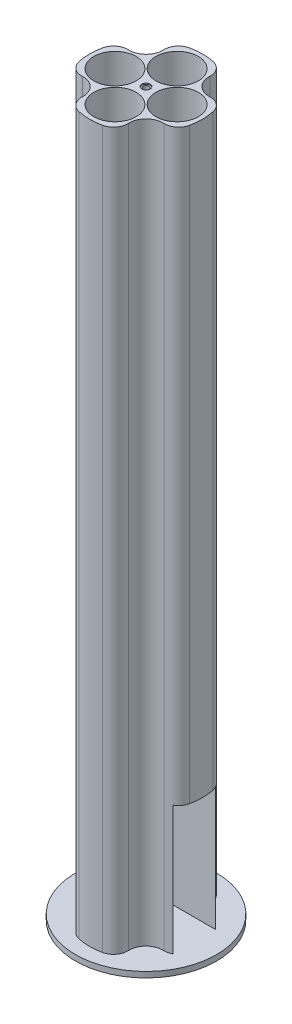
SolidWorks part; units mm, degrees
material "Acrylic (Medium-high impact)"
ref_plane "Front Plane" through (0, 0, 0) normal (0, 0, 1) x (1, 0, 0)
ref_plane "Top Plane" through (0, 0, 0) normal (0, 1, 0) x (1, 0, 0)
ref_plane "Right Plane" through (0, 0, 0) normal (1, 0, 0) x (0, 0, -1)
sketch "Sketch1" plane through (0, 0, 0) normal (0, 1, 0) x (1, 0, 0)
  circle A0 centre (0, 0) radius 100
  dimension "D1" = 200
extrude "Boss-Extrude2" add sketch "Sketch1" along normal blind 1120 contours A0
sketch "Sketch4" plane through (0, 1120, 0) normal (0, 1, 0) x (1, 0, 0)
  line L0 (0, 0) -> (0, -55) construction
  line L1 (0, 0) -> (55, 0) construction
  line L2 (0, 0) -> (0, 55) construction
  line L3 (0, 0) -> (-55, 0) construction
  circle A0 centre (55, 0) radius 37.5
  circle A1 centre (0, 55) radius 37.5
  circle A2 centre (-55, 0) radius 37.5
  circle A3 centre (0, -55) radius 37.5
  dimension "D2" = 75
  dimension "D1" = 55
extrude "Cut-Extrude1" cut sketch "Sketch4" against normal blind 1100 contours A1 | A2 | A0 | A3
sketch "Sketch6" plane through (0, 1120, 0) normal (0, 1, 0) x (1, 0, 0)
  line L0 (0, 0) -> (-70.7107, 70.7107) construction
  circle A0 centre (0, 0) radius 15
  circle A1 centre (-70.7107, 70.7107) radius 30.03
  circle A2 centre (0, 0) radius 100
  circle A3 centre (0, 0) radius 100
  circle A4 centre (0, 0) radius 15
  circle A5 centre (70.7107, 70.7107) radius 30.03
  circle A6 centre (0, 0) radius 15
  circle A7 centre (70.7107, -70.7107) radius 30.03
  circle A8 centre (0, 0) radius 15
  circle A9 centre (-70.7107, -70.7107) radius 30.03
  point P20 (0, 0)
  circle M8 centre (0, 0) radius 100
  dimension "D1" = 30
  dimension "D2" = 0
  dimension "D3" = 4
extrude "Cut-Extrude2" cut sketch "Sketch6" against normal through all contours L0 A1 M8 | A1 L0 A3 | A3 A5 | A3 A7 | A3 A9
sketch "Sketch7" plane through (0, 1120, 0) normal (0, 1, 0) x (1, 0, 0)
  circle A0 centre (0, 0) radius 5
  dimension "D1" = 10
extrude "Cut-Extrude3" cut sketch "Sketch7" against normal blind 1200
fillet "Fillet1" radius 25 8 edges at (-88.516, 560, 46.5286) (-46.5286, 560, 88.516) (-46.5286, 560, -88.516) (-88.516, 560, -46.5286) (88.516, 560, -46.5286) (46.5286, 560, -88.516) (46.5286, 560, 88.516) (88.516, 560, 46.5286)
sketch "Sketch8" plane through (0, 1120, 0) normal (0, 1, 0) x (1, 0, 0)
  line L1 (147.8756, 155.206) -> (-128.3047, 155.206)
  line L2 (147.8756, 155.206) -> (147.8756, -161.0426)
  line L3 (147.8756, -161.0426) -> (-128.3047, -161.0426)
  line L4 (-128.3047, 155.206) -> (-128.3047, -161.0426)
extrude "Cut-Extrude4" cut sketch "Sketch8" against normal blind 65
sketch "Sketch9" plane through (0, 1055, 0) normal (0, 1, 0) x (1, 0, 0)
  circle A0 centre (0, 0) radius 7.5
  dimension "D1" = 15
extrude "Cut-Extrude5" cut sketch "Sketch9" against normal blind 2
sketch "Sketch10" plane through (0, 0, 0) normal (0, -1, 0) x (1, 0, 0)
  arc A16 (20.9906, 97.7722) -> (-20.9906, 97.7722) centre (0, 0) ccw
  arc A17 (-20.9906, 97.7722) -> (-40.7146, 72.1396) centre (-15.743, 73.3291) ccw
  arc A18 (-72.1396, 40.7146) -> (-40.7146, 72.1396) centre (-70.7107, 70.7107) ccw
  arc A19 (-72.1396, 40.7146) -> (-97.7722, 20.9906) centre (-73.3291, 15.743) ccw
  arc A20 (-97.7722, 20.9906) -> (-97.7722, -20.9906) centre (0, 0) ccw
  arc A21 (-97.7722, -20.9906) -> (-72.1396, -40.7146) centre (-73.3291, -15.743) ccw
  arc A22 (-40.7146, -72.1396) -> (-72.1396, -40.7146) centre (-70.7107, -70.7107) ccw
  arc A23 (-40.7146, -72.1396) -> (-20.9906, -97.7722) centre (-15.743, -73.3291) ccw
  arc A24 (-20.9906, -97.7722) -> (20.9906, -97.7722) centre (0, 0) ccw
  arc A25 (20.9906, -97.7722) -> (40.7146, -72.1396) centre (15.743, -73.3291) ccw
  arc A26 (72.1396, -40.7146) -> (40.7146, -72.1396) centre (70.7107, -70.7107) ccw
  arc A27 (72.1396, -40.7146) -> (97.7722, -20.9906) centre (73.3291, -15.743) ccw
  arc A28 (97.7722, -20.9906) -> (97.7722, 20.9906) centre (0, 0) ccw
  arc A29 (97.7722, 20.9906) -> (72.1396, 40.7146) centre (73.3291, 15.743) ccw
  arc A30 (40.7146, 72.1396) -> (72.1396, 40.7146) centre (70.7107, 70.7107) ccw
  arc A31 (40.7146, 72.1396) -> (20.9906, 97.7722) centre (15.743, 73.3291) ccw
  arc A32 (20.9906, 97.7722) -> (-20.9906, 97.7722) centre (0, 0) ccw
  arc A33 (-20.9906, 97.7722) -> (-40.7146, 72.1396) centre (-15.743, 73.3291) ccw
  arc A34 (-72.1396, 40.7146) -> (-40.7146, 72.1396) centre (-70.7107, 70.7107) ccw
  arc A35 (-72.1396, 40.7146) -> (-97.7722, 20.9906) centre (-73.3291, 15.743) ccw
  arc A36 (-97.7722, 20.9906) -> (-97.7722, -20.9906) centre (0, 0) ccw
  arc A37 (-97.7722, -20.9906) -> (-72.1396, -40.7146) centre (-73.3291, -15.743) ccw
  arc A38 (-40.7146, -72.1396) -> (-72.1396, -40.7146) centre (-70.7107, -70.7107) ccw
  arc A39 (-40.7146, -72.1396) -> (-20.9906, -97.7722) centre (-15.743, -73.3291) ccw
  arc A40 (-20.9906, -97.7722) -> (20.9906, -97.7722) centre (0, 0) ccw
  arc A41 (20.9906, -97.7722) -> (40.7146, -72.1396) centre (15.743, -73.3291) ccw
  arc A42 (72.1396, -40.7146) -> (40.7146, -72.1396) centre (70.7107, -70.7107) ccw
  arc A43 (72.1396, -40.7146) -> (97.7722, -20.9906) centre (73.3291, -15.743) ccw
  arc A44 (97.7722, -20.9906) -> (97.7722, 20.9906) centre (0, 0) ccw
  arc A45 (97.7722, 20.9906) -> (72.1396, 40.7146) centre (73.3291, 15.743) ccw
  arc A46 (40.7146, 72.1396) -> (72.1396, 40.7146) centre (70.7107, 70.7107) ccw
  arc A47 (40.7146, 72.1396) -> (20.9906, 97.7722) centre (15.743, 73.3291) ccw
  dimension "D1" = 0
extrude "Boss-Extrude3" add sketch "Sketch10" along normal blind 223.2146
sketch "Sketch11" plane through (0, -223.2146, 0) normal (0, -1, 0) x (1, 0, 0)
  circle A0 centre (0, 0) radius 125
  dimension "D1" = 250
extrude "Boss-Extrude4" add sketch "Sketch11" against normal blind 10
sketch "Sketch12" plane through (0, 0, 0) normal (1, 0, 0) x (0, 0, -1)
  line L0 (37.5, 20) -> (-37.5, 20) construction
  line L1 (37.5, 20) -> (-37.5, 20)
  line L2 (-37.5, 20) -> (-37.5, -213.2146)
  line L3 (-20.9906, -213.2146) -> (-40.743, -213.2146) construction
  line L4 (37.5, 20) -> (37.5, -213.2146)
  line L5 (40.743, -213.2146) -> (20.9906, -213.2146) construction
  line L6 (-37.5, 15) -> (37.5, 15)
  line L7 (-37.5, -213.2146) -> (37.5, -213.2146)
  dimension "D1" = 5
extrude "Cut-Extrude6" cut sketch "Sketch12" against normal mid plane 246 contours L2 L7 L4 L6
